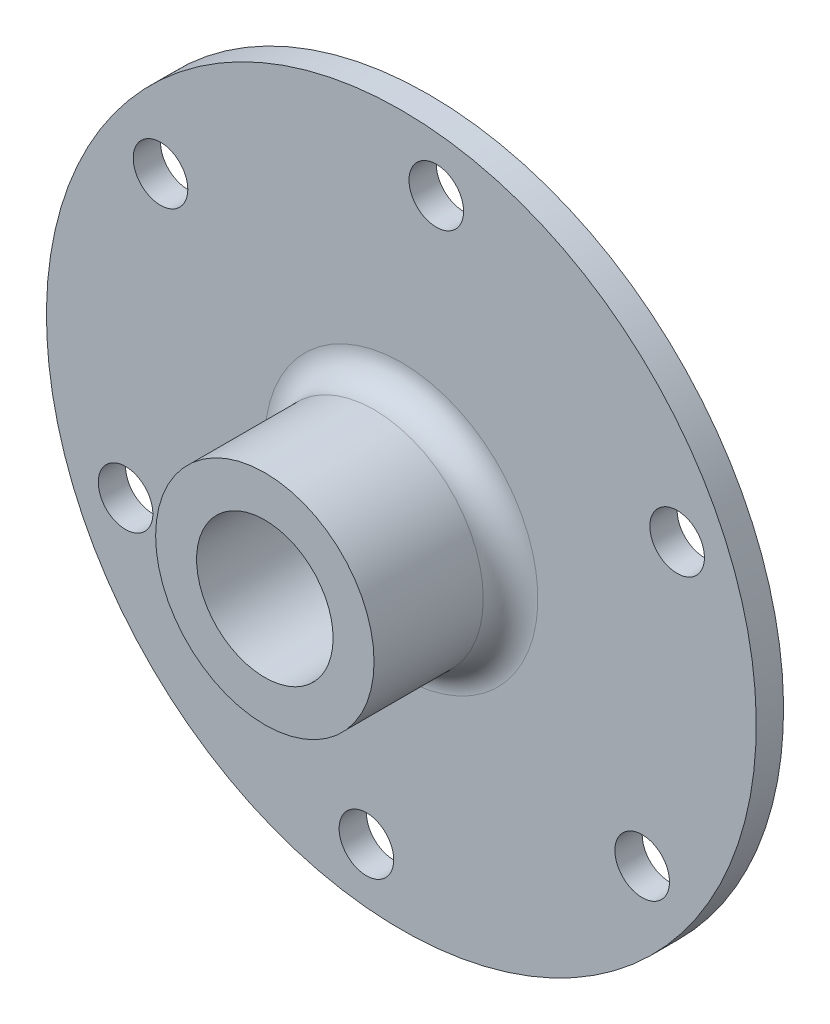
SolidWorks part; units mm, degrees
material "AISI 1020"
ref_plane "Front Plane" through (0, 0, 0) normal (0, 0, 1) x (1, 0, 0)
ref_plane "Top Plane" through (0, 0, 0) normal (0, 1, 0) x (1, 0, 0)
ref_plane "Right Plane" through (0, 0, 0) normal (1, 0, 0) x (0, 0, -1)
sketch "Sketch2" plane through (0, 0, 0) normal (1, 0, 0) x (0, 0, -1)
  line L2 (0, 0) -> (0, 41.275)
  line L3 (0, 41.275) -> (-3.175, 41.275)
  line L4 (-3.175, 12.7) -> (-3.175, 41.275)
  line L5 (0, 0) -> (-19.05, 0)
  line L7 (-3.175, 12.7) -> (-19.05, 12.7)
  line L8 (-19.05, 0) -> (-19.05, 12.7)
  dimension "D1" = 19.05
  dimension "D2" = 41.275
  dimension "D3" = 3.175
  dimension "D4" = 12.7
revolve "Revolve1" add sketch "Sketch2" angle 360 about L5
sketch "Sketch3" plane through (0, 0, 19.05) normal (0, 0, 1) x (1, 0, 0)
  circle A0 centre (0, 0) radius 7.9375
  circle A1 centre (0, 0) radius 34.925 construction
  circle A2 centre (-28.0086, 20.8632) radius 3.175
extrude "Cut-Extrude1" cut sketch "Sketch3" against normal through all
pattern_circular "CirPattern1" count 6 over 360 about axis through (0, 0, 0) along (0, 0, 1) of "Cut-Extrude1"
fillet "Fillet1" radius 3.175 1 edges at (0, 12.7, 3.175)
